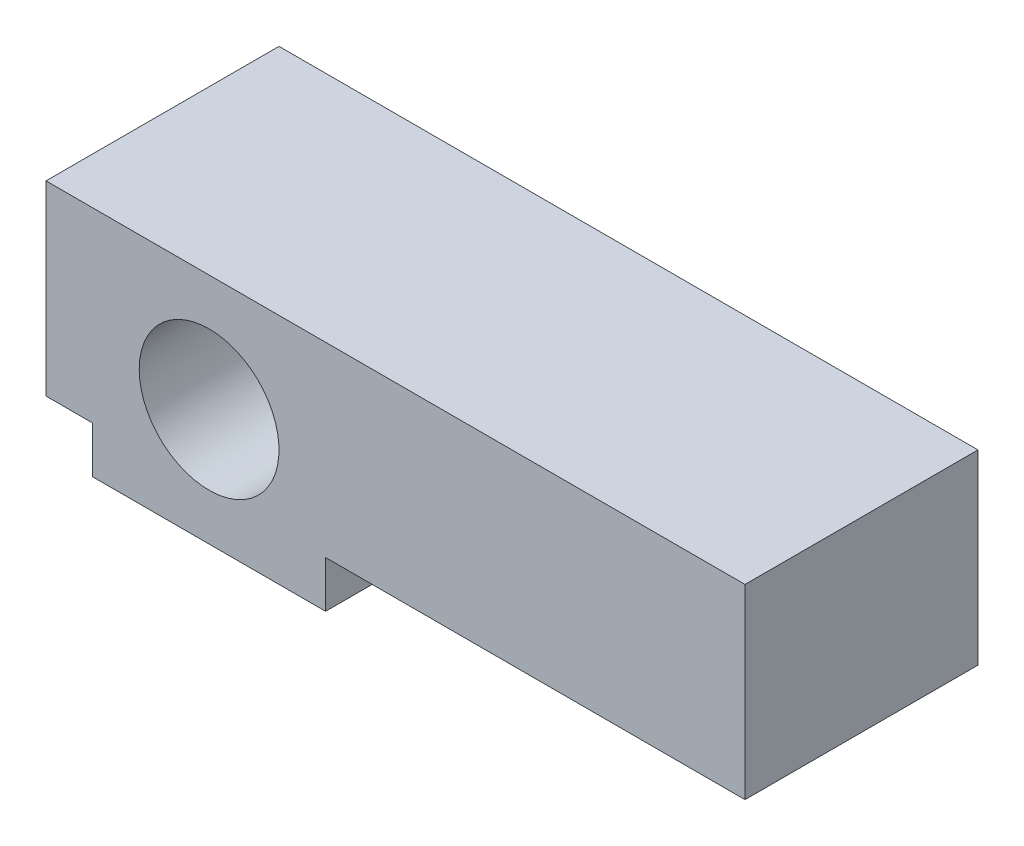
SolidWorks part; units mm, degrees
ref_plane "前视基准面" through (0, 0, 0) normal (0, 0, 1) x (1, 0, 0)
ref_plane "上视基准面" through (0, 0, 0) normal (0, 1, 0) x (1, 0, 0)
ref_plane "右视基准面" through (0, 0, 0) normal (1, 0, 0) x (0, 0, -1)
sketch "草图2" plane through (0, 0, 95) normal (0, 0, -1) x (-1, 0, 0)
  line L12 (2, -10) -> (12, -10)
  line L13 (12, -10) -> (12, -8)
  line L14 (12, -8) -> (14, -8)
  line L15 (14, -8) -> (14, 0)
  line L16 (14, 0) -> (0, 0)
  line L17 (0, 0) -> (0, -8)
  line L18 (0, -8) -> (2, -8)
  line L19 (2, -8) -> (2, -10)
  dimension "D1" = 14
  dimension "D2" = 2
  dimension "D3" = 2
  dimension "D4" = 2
  dimension "D5" = 8
extrude "凸台-拉伸1" add sketch "草图2" along normal blind 10 contours L16 L17 L18 L19 L12 L13 L14 L15
sketch "草图3" plane through (0, 0, 85) normal (0, 0, -1) x (-1, 0, 0)
  line L0 (2, -10) -> (12, -10) construction
  line L3 (0, 0) -> (0, -8) construction
  circle A0 centre (7, -5) radius 3
  dimension "D1" = 6
  dimension "D2" = 5
  dimension "D3" = 7
extrude "切除-拉伸1" cut sketch "草图3" against normal up to next contours A0
sketch "草图4" plane through (0, 0, 0) normal (1, 0, 0) x (0, 0, -1)
  line L4 (-95, 0) -> (-95, -8)
  line L5 (-95, -8) -> (-85, -8)
  line L6 (-85, -8) -> (-85, 0)
  line L7 (-85, 0) -> (-95, 0)
  line L8 (-95, 0) -> (-95, -8)
  line L9 (-95, -8) -> (-85, -8)
  line L10 (-85, -8) -> (-85, 0)
  line L11 (-85, 0) -> (-95, 0)
  dimension "D1" = 0
extrude "凸台-拉伸2" add sketch "草图4" along normal blind 16
